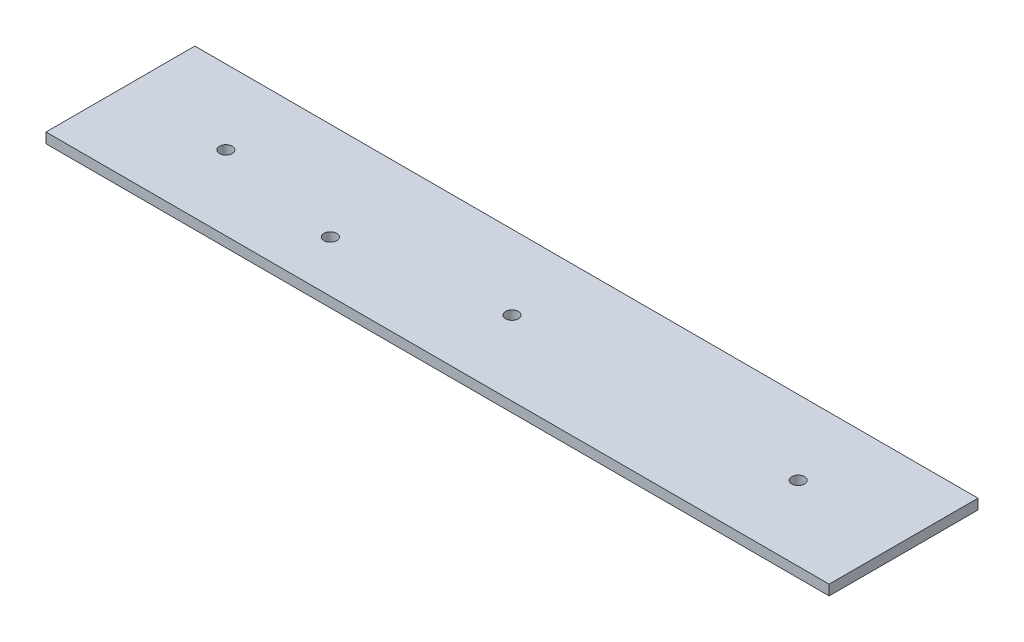
SolidWorks part; units mm, degrees
ref_plane "Front Plane" through (0, 0, 0) normal (0, 0, 1) x (1, 0, 0)
ref_plane "Top Plane" through (0, 0, 0) normal (0, 1, 0) x (1, 0, 0)
ref_plane "Right Plane" through (0, 0, 0) normal (1, 0, 0) x (0, 0, -1)
sketch "Sketch1" plane through (0, 0, 0) normal (0, 1, 0) x (1, 0, 0)
  line L0 (-71, 0) -> (71, 0) construction
  line L2 (-97.1504, -18.4656) -> (97.1504, -18.4656)
  line L3 (-97.1504, -18.4656) -> (-97.1504, 18.4656)
  line L4 (-97.1504, 18.4656) -> (97.1504, 18.4656)
  line L5 (97.1504, -18.4656) -> (97.1504, 18.4656)
  line L6 (-97.1504, -18.4656) -> (97.1504, 18.4656) construction
  line L7 (-97.1504, 18.4656) -> (97.1504, -18.4656) construction
  circle A0 centre (-71, 0) radius 1.5875
  circle A1 centre (71, 0) radius 1.5875
  circle A2 centre (0, 0) radius 1.5875
  circle A3 centre (-39.31, -5.75) radius 1.5875
  point P2 (0, 0)
  point P6 (0, 0)
  dimension "D2" = 3.175
  dimension "D1" = 142
  dimension "D3" = 39.31
  dimension "D4" = 5.75
extrude "Boss-Extrude1" add sketch "Sketch1" along normal mid plane 2.54
sketch "Sketch2" plane through (0, -1.27, 0) normal (0, -1, 0) x (-1, 0, 0)
  line L0 (39.31, -5.75) -> (26.2458, -5.75) construction
